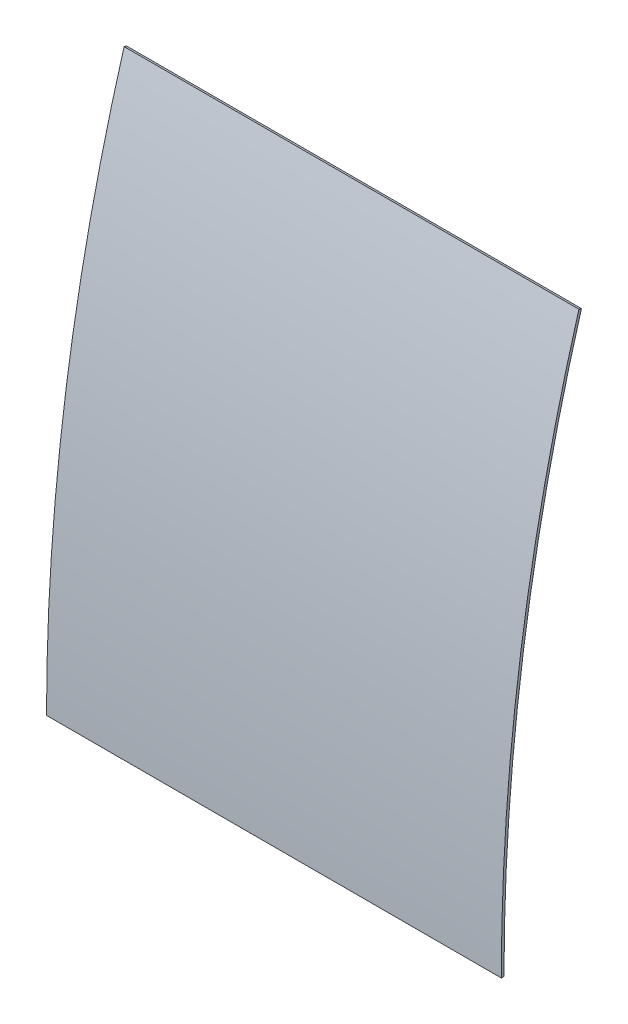
SolidWorks part; units mm, degrees
material "Acrylic (Medium-high impact)"
ref_plane "Front Plane" through (0, 0, 0) normal (0, 0, 1) x (1, 0, 0)
ref_plane "Top Plane" through (0, 0, 0) normal (0, 1, 0) x (1, 0, 0)
ref_plane "Right Plane" through (0, 0, 0) normal (1, 0, 0) x (0, 0, -1)
sketch "Sketch1" plane through (0, 0, 0) normal (1, 0, 0) x (0, 0, -1)
  line L0 (46.0375, 320.675) -> (1139.8524, 0) construction
  line L1 (1139.8524, 0) -> (0, 0) construction
  arc A1 (0, 0) -> (46.0375, 320.675) centre (1139.8524, 0) cw
  point P0 (0, 0)
  point P1 (46.0375, 320.675)
  dimension "D3" = 16.34
  dimension "D1" = 320.675
  dimension "D2" = 46.0375
extrude "Extrude-Thin1" add sketch "Sketch1" along normal blind 269.875 thin
